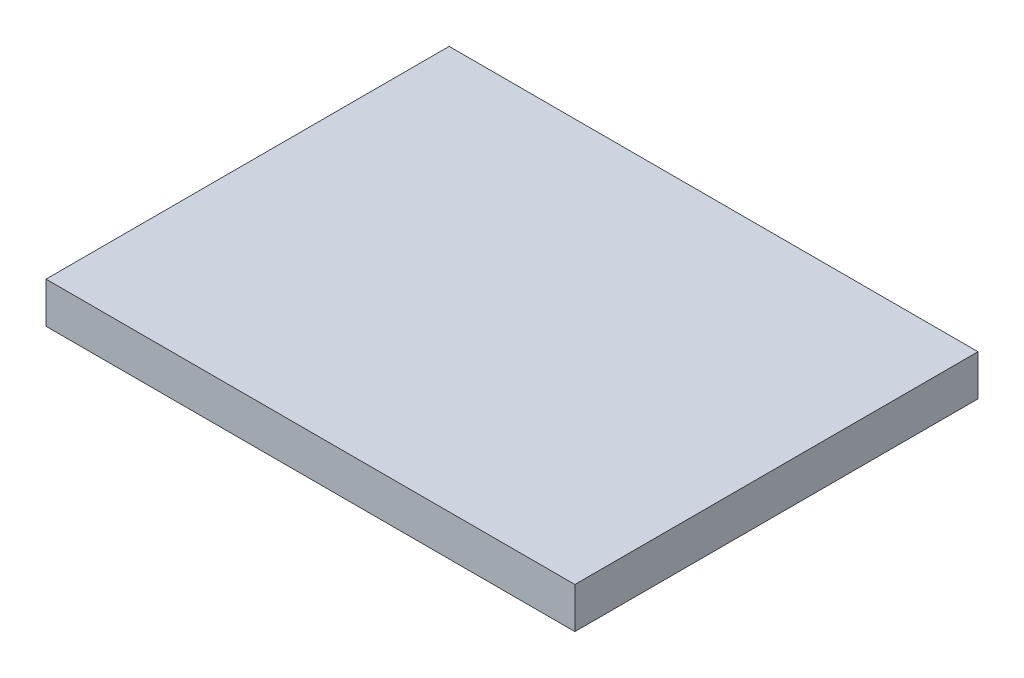
SolidWorks part; units mm, degrees
ref_plane "Front Plane" through (0, 0, 0) normal (0, 0, 1) x (1, 0, 0)
ref_plane "Top Plane" through (0, 0, 0) normal (0, 1, 0) x (1, 0, 0)
ref_plane "Right Plane" through (0, 0, 0) normal (1, 0, 0) x (0, 0, -1)
sketch "Sketch1" plane through (0, 0, 0) normal (0, 1, 0) x (1, 0, 0)
  line L1 (-64.7575, -49.3606) -> (64.7575, -49.3606)
  line L2 (-64.7575, -49.3606) -> (-64.7575, 49.3606)
  line L3 (-64.7575, 49.3606) -> (64.7575, 49.3606)
  line L4 (64.7575, -49.3606) -> (64.7575, 49.3606)
  line L5 (-64.7575, -49.3606) -> (64.7575, 49.3606) construction
  line L6 (-64.7575, 49.3606) -> (64.7575, -49.3606) construction
  point P0 (0, 0)
extrude "Boss-Extrude1" add sketch "Sketch1" along normal blind 10
